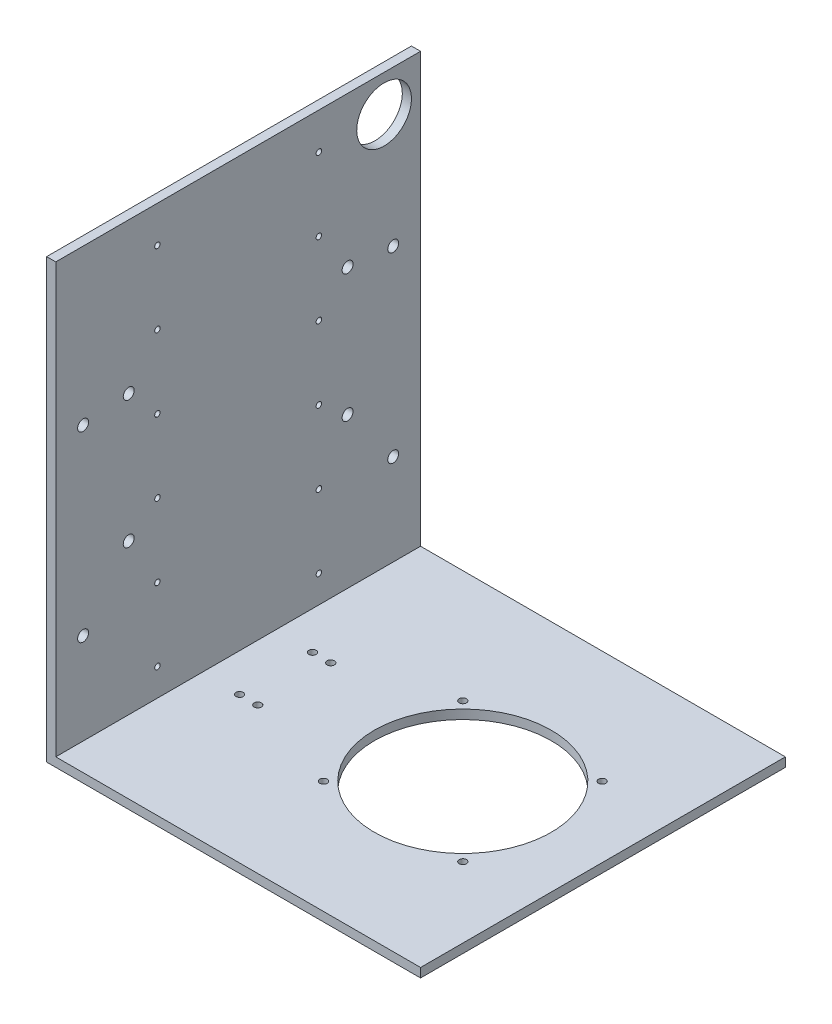
SolidWorks part; units mm, degrees
ref_plane "Front Plane" through (0, 0, 0) normal (0, 0, 1) x (1, 0, 0)
ref_plane "Top Plane" through (0, 0, 0) normal (0, 1, 0) x (1, 0, 0)
ref_plane "Right Plane" through (0, 0, 0) normal (1, 0, 0) x (0, 0, -1)
sketch "Sketch1" plane through (0, 0, 0) normal (0, 0, 1) x (1, 0, 0)
  line L0 (0, 240) -> (0, 0)
  line L1 (0, 0) -> (205, 0)
  line L2 (205, 0) -> (205, 5)
  line L3 (205, 5) -> (5, 5)
  line L4 (5, 5) -> (5, 240)
  line L5 (5, 240) -> (0, 240)
  dimension "D1" = 5
  dimension "D2" = 5
  dimension "D3" = 200
  dimension "D4" = 235
extrude "Boss-Extrude1" add sketch "Sketch1" along normal blind 200
sketch "Sketch2" plane through (0, 5, 0) normal (0, 1, 0) x (1, 0, 0)
  line L0 (205, -100) -> (0, -100) construction
  line L1 (205, -200) -> (205, 0) construction
  line L2 (0, -200) -> (0, 0) construction
  line L4 (166.3526, -138.1825) -> (89.9826, -138.1825) construction
  line L5 (166.3526, -138.1825) -> (166.3526, -61.8175) construction
  line L6 (166.3526, -61.8175) -> (89.9826, -61.8175) construction
  line L7 (89.9826, -138.1825) -> (89.9826, -61.8175) construction
  line L8 (166.3526, -138.1825) -> (89.9826, -61.8175) construction
  line L9 (166.3526, -61.8175) -> (89.9826, -138.1825) construction
  circle A0 centre (128.1676, -100) radius 48.5
  circle A1 centre (89.9826, -61.8175) radius 2
  circle A2 centre (166.3526, -61.8175) radius 2
  circle A3 centre (89.9826, -138.1825) radius 2
  circle A4 centre (166.3526, -138.1825) radius 2
  dimension "D1" = 97
  dimension "D2" = 4
  dimension "D3" = 108
  dimension "D4" = 76.37
extrude "Cut-Extrude1" cut sketch "Sketch2" against normal up to next
sketch "Sketch3" plane through (0, 5, 0) normal (0, 1, 0) x (1, 0, 0)
  line L0 (30.75, 0) -> (30.75, -200) construction
  line L1 (205, 0) -> (5, 0) construction
  line L2 (205, -200) -> (5, -200) construction
  line L3 (30.75, -200) -> (30.75, -71.2391) construction
  line L4 (-16.5042, -100) -> (30.75, -100) construction
  line L6 (5, -200) -> (5, 0) construction
  circle A0 centre (25.75, -80) radius 2
  circle A1 centre (25.75, -120) radius 2
  circle A2 centre (35.75, -120) radius 2
  circle A3 centre (35.75, -80) radius 2
  point P10 (7.1229, -100)
  dimension "D2" = 40
  dimension "D3" = 10
  dimension "D4" = 4
  dimension "D1" = 25.75
extrude "Cut-Extrude2" cut sketch "Sketch3" against normal up to next
sketch "Sketch4" plane through (5, 0, 0) normal (1, 0, 0) x (0, 0, -1)
  line L0 (0, 5) -> (0, 240) construction
  line L1 (-200, 240) -> (0, 240) construction
  circle A0 centre (-20, 220) radius 15
  dimension "D1" = 30
  dimension "D2" = 20
  dimension "D3" = 20
extrude "Cut-Extrude3" cut sketch "Sketch4" against normal blind 10
sketch "Sketch5" plane through (5, 0, 0) normal (1, 0, 0) x (0, 0, -1)
  line L0 (-100, 240) -> (-100, 5) construction
  line L1 (-200, 240) -> (0, 240) construction
  line L2 (-200, 5) -> (0, 5) construction
  line L3 (-185, 240) -> (-185, 5) construction
  line L4 (-200, 5) -> (-200, 240) construction
  circle A0 centre (-185, 55) radius 3
  circle A1 centre (-185, 155) radius 3
  circle A2 centre (-15, 55) radius 3
  circle A3 centre (-15, 155) radius 3
  dimension "D2" = 100
  dimension "D3" = 6
  dimension "D1" = 50
  dimension "D4" = 15
extrude "Cut-Extrude4" cut sketch "Sketch5" against normal up to next
sketch "Sketch6" plane through (5, 0, 0) normal (1, 0, 0) x (0, 0, -1)
  line L0 (-100, 240) -> (-100, 5) construction
  line L1 (-200, 240) -> (0, 240) construction
  line L2 (-200, 5) -> (0, 5) construction
  circle A0 centre (-144.25, 220) radius 1.5
  circle A1 centre (-55.75, 220) radius 1.5
  circle A2 centre (-144.25, 180) radius 1.5
  circle A3 centre (-55.75, 180) radius 1.5
  circle A4 centre (-144.25, 140) radius 1.5
  circle A5 centre (-55.75, 140) radius 1.5
  circle A6 centre (-144.25, 100) radius 1.5
  circle A7 centre (-55.75, 100) radius 1.5
  circle A8 centre (-144.25, 60) radius 1.5
  circle A9 centre (-55.75, 60) radius 1.5
  circle A10 centre (-144.25, 20) radius 1.5
  circle A11 centre (-55.75, 20) radius 1.5
  dimension "D1" = 88.5
  dimension "D2" = 20
  dimension "D3" = 3
  dimension "D5" = 40
  dimension "D4" = 6
extrude "Cut-Extrude5" cut sketch "Sketch6" against normal up to next
sketch "Sketch8" plane through (5, 0, 0) normal (1, 0, 0) x (0, 0, -1)
  line L0 (-100, 240) -> (-100, 5) construction
  line L1 (-200, 240) -> (0, 240) construction
  line L2 (-200, 5) -> (0, 5) construction
  line L3 (-200, 122.5) -> (0, 122.5) construction
  line L4 (-200, 5) -> (-200, 240) construction
  line L5 (0, 5) -> (0, 240) construction
  circle A0 centre (-160, 157.5) radius 3
  circle A1 centre (-40, 157.5) radius 3
  circle A2 centre (-40, 87.5) radius 3
  circle A3 centre (-160, 87.5) radius 3
  dimension "D1" = 70
  dimension "D2" = 120
  dimension "D3" = 6
extrude "Cut-Extrude6" cut sketch "Sketch8" against normal up to next
